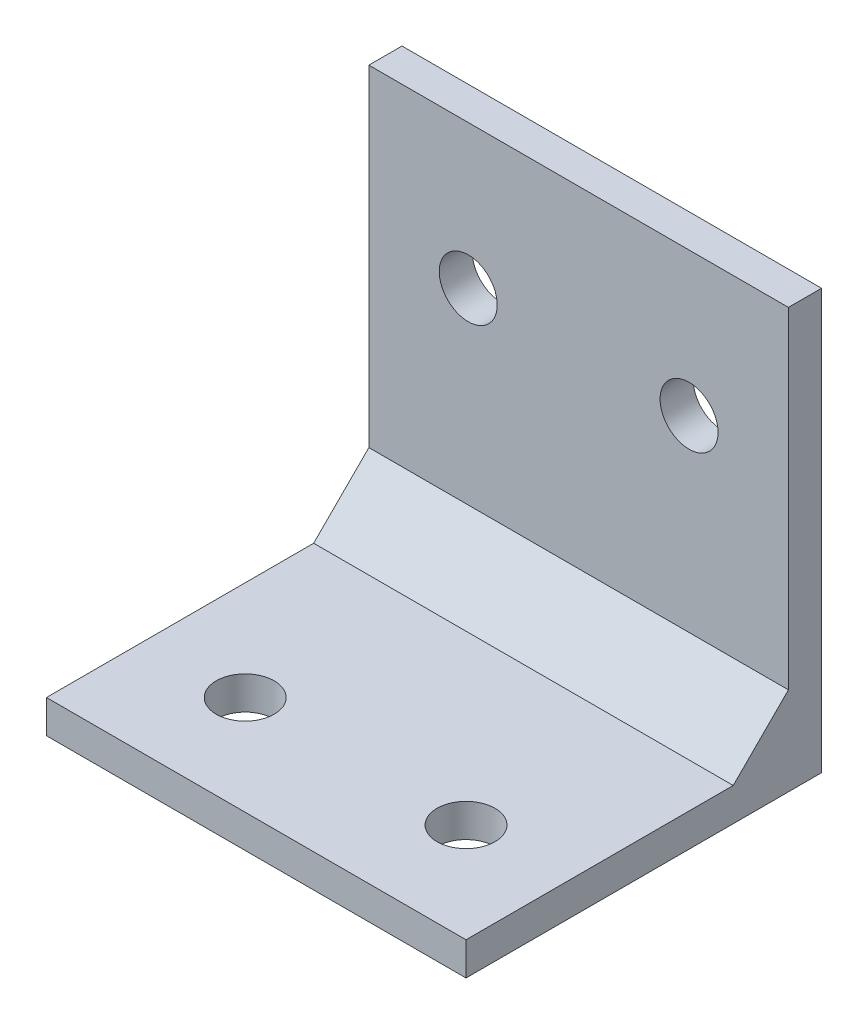
SolidWorks part; units mm, degrees
ref_plane "Front Plane" through (0, 0, 0) normal (0, 0, 1) x (1, 0, 0)
ref_plane "Top Plane" through (0, 0, 0) normal (0, 1, 0) x (1, 0, 0)
ref_plane "Right Plane" through (0, 0, 0) normal (1, 0, 0) x (0, 0, -1)
sketch "Sketch1" plane through (0, 0, 0) normal (0, 1, 0) x (1, 0, 0)
  line L0 (-19, 0) -> (-19, -32.2) construction
  line L1 (0, 0) -> (-38, 0)
  line L2 (0, 0) -> (0, -32.2)
  line L3 (0, -32.2) -> (-38, -32.2)
  line L4 (-38, 0) -> (-38, -32.2)
  circle A0 centre (-29, -23.2) radius 2.625
  circle A2 centre (-9, -23.2) radius 2.625
  dimension "D3" = 5.25
  dimension "D4" = 9
  dimension "D5" = 10
  dimension "D6" = 9
  dimension "D1" = 32.2
  dimension "D2" = 38
extrude "Boss-Extrude1" add sketch "Sketch1" along normal blind 3
sketch "Sketch2" plane through (0, 3, 0) normal (0, 1, 0) x (1, 0, 0)
  line L0 (0, -32.2) -> (0, 0) construction
  line L1 (-38, 0) -> (0, 0)
  line L2 (-38, 0) -> (-38, -3)
  line L3 (-38, -3) -> (0, -3)
  line L4 (0, 0) -> (0, -3)
  dimension "D1" = 3
extrude "Boss-Extrude2" add sketch "Sketch2" along normal blind 35
sketch "Sketch3" plane through (0, 0, 3) normal (0, 0, 1) x (1, 0, 0)
  line L0 (-19, 38) -> (-19, 3) construction
  line L1 (-38, 38) -> (0, 38) construction
  line L2 (-38, 3) -> (0, 3) construction
  line L5 (-38, 3) -> (0, 3) construction
  circle A4 centre (-29, 25) radius 2.625
  circle A5 centre (-9, 25) radius 2.625
  dimension "D1" = 5.25
  dimension "D2" = 22
  dimension "D3" = 10
extrude "Cut-Extrude1" cut sketch "Sketch3" against normal through all
sketch "Sketch4" plane through (0, 0, 0) normal (1, 0, 0) x (0, 0, -1)
  line L0 (-3, 8) -> (-8, 3)
  line L1 (-3, 38) -> (-3, 3) construction
  line L2 (-32.2, 3) -> (-3, 3) construction
  line L3 (-8, 3) -> (-3, 3)
  line L4 (-3, 3) -> (-3, 8)
  dimension "D1" = 5
  dimension "D2" = 5
extrude "Boss-Extrude3" add sketch "Sketch4" against normal through all
